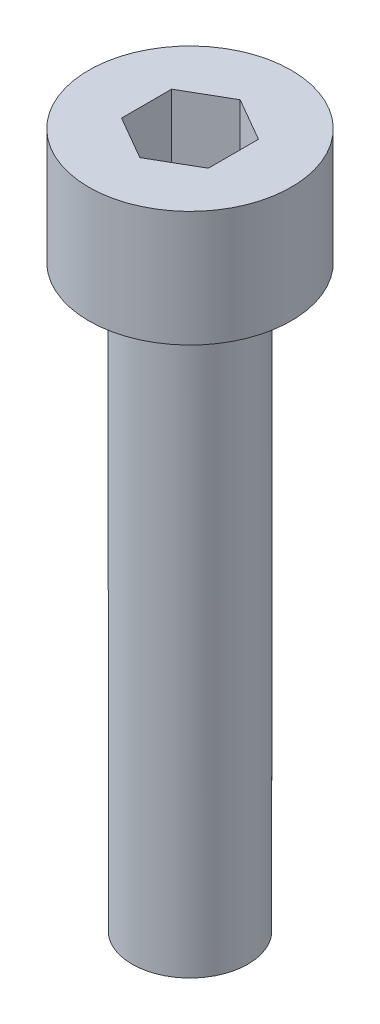
SolidWorks part; units mm, degrees
ref_plane "Front Plane" through (0, 0, 0) normal (0, 0, 1) x (1, 0, 0)
ref_plane "Top Plane" through (0, 0, 0) normal (0, 1, 0) x (1, 0, 0)
ref_plane "Right Plane" through (0, 0, 0) normal (1, 0, 0) x (0, 0, -1)
sketch "Sketch2" plane through (0, 0, 0) normal (0, 1, 0) x (1, 0, 0)
  line L1 (0, 1.7321) -> (-1.5, 0.866)
  line L2 (-1.5, 0.866) -> (-1.5, -0.866)
  line L3 (-1.5, -0.866) -> (0, -1.7321)
  line L4 (0, -1.7321) -> (1.5, -0.866)
  line L5 (1.5, -0.866) -> (1.5, 0.866)
  line L6 (1.5, 0.866) -> (0, 1.7321)
  circle A0 centre (0, 0) radius 3.5
  circle A1 centre (0, 0) radius 1.5 construction
  dimension "D1" = 7
  dimension "D2" = 3
extrude "Boss-Extrude1" add sketch "Sketch2" along normal blind 4
sketch "Sketch3" plane through (0, 0, 0) normal (0, -1, 0) x (1, 0, 0)
  circle A0 centre (0, 0) radius 2
  dimension "D1" = 4
extrude "Boss-Extrude2" add sketch "Sketch3" along normal blind 20
